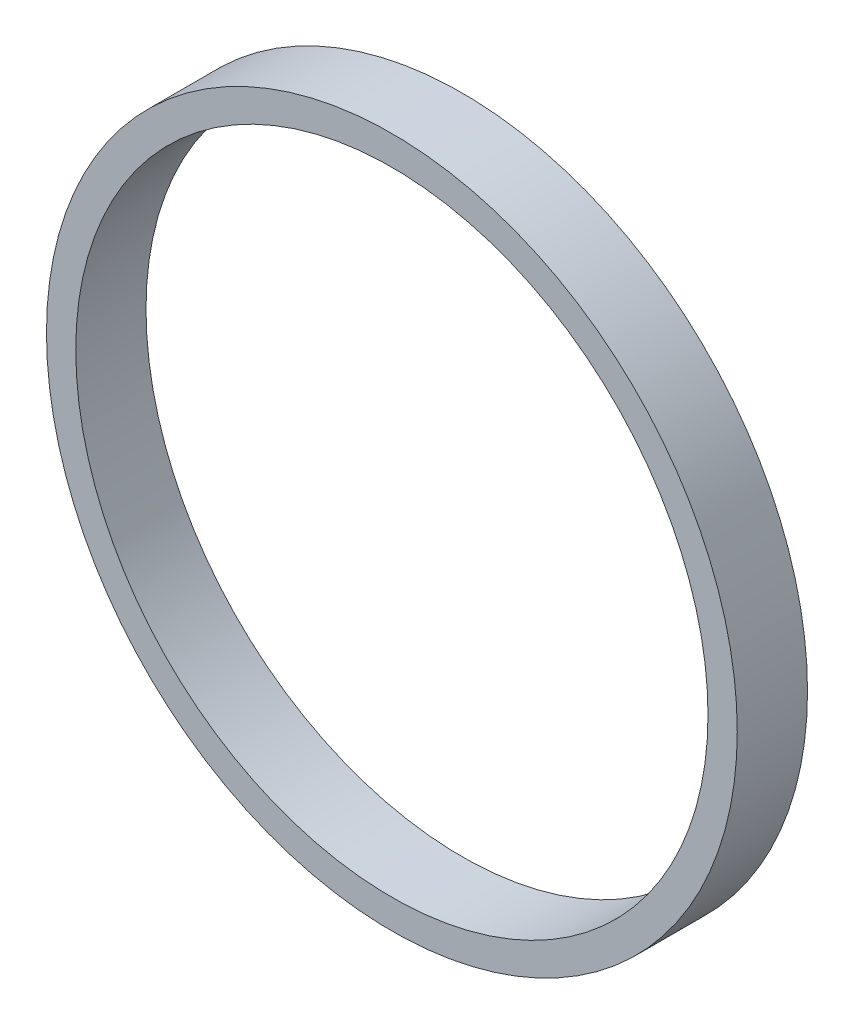
SolidWorks part; units mm, degrees
ref_plane "Front Plane" through (0, 0, 0) normal (0, 0, 1) x (1, 0, 0)
ref_plane "Top Plane" through (0, 0, 0) normal (0, 1, 0) x (1, 0, 0)
ref_plane "Right Plane" through (0, 0, 0) normal (1, 0, 0) x (0, 0, -1)
sketch "Sketch1" plane through (0, 0, 0) normal (0, 0, 1) x (1, 0, 0)
  circle A0 centre (0, 0) radius 59
  circle A1 centre (0, 0) radius 54
  dimension "D1" = 118
  dimension "D2" = 5
extrude "Boss-Extrude1" add sketch "Sketch1" along normal blind 12
